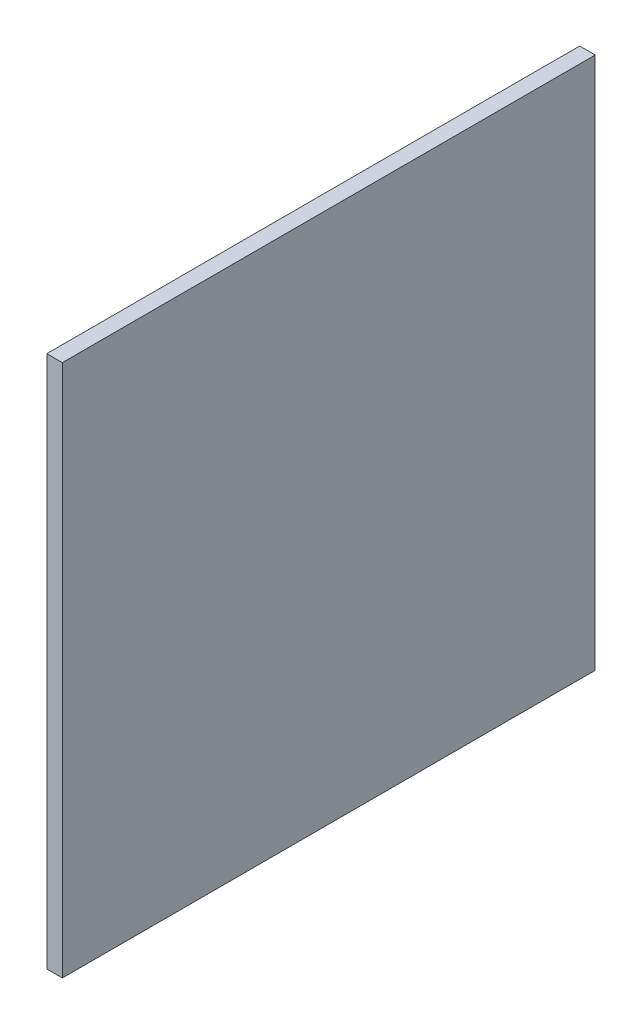
SolidWorks part; units mm, degrees
ref_plane "Front Plane" through (0, 0, 0) normal (0, 0, 1) x (1, 0, 0)
ref_plane "Top Plane" through (0, 0, 0) normal (0, 1, 0) x (1, 0, 0)
ref_plane "Right Plane" through (0, 0, 0) normal (1, 0, 0) x (0, 0, -1)
sketch "Sketch1" plane through (0, 0, 0) normal (1, 0, 0) x (0, 0, -1)
  line L0 (66.6542, 183.9416) -> (333.9875, 183.9416) construction
  line L1 (0, 0) -> (68.6, 0)
  line L2 (0, 0) -> (0, 68.6)
  line L3 (0, 68.6) -> (68.6, 68.6)
  line L4 (68.6, 0) -> (68.6, 68.6)
  dimension "D1" = 68.6
  dimension "D2" = 68.6
extrude "Boss-Extrude1" add sketch "Sketch1" against normal blind 2 contours L2 L1 L4 L3
